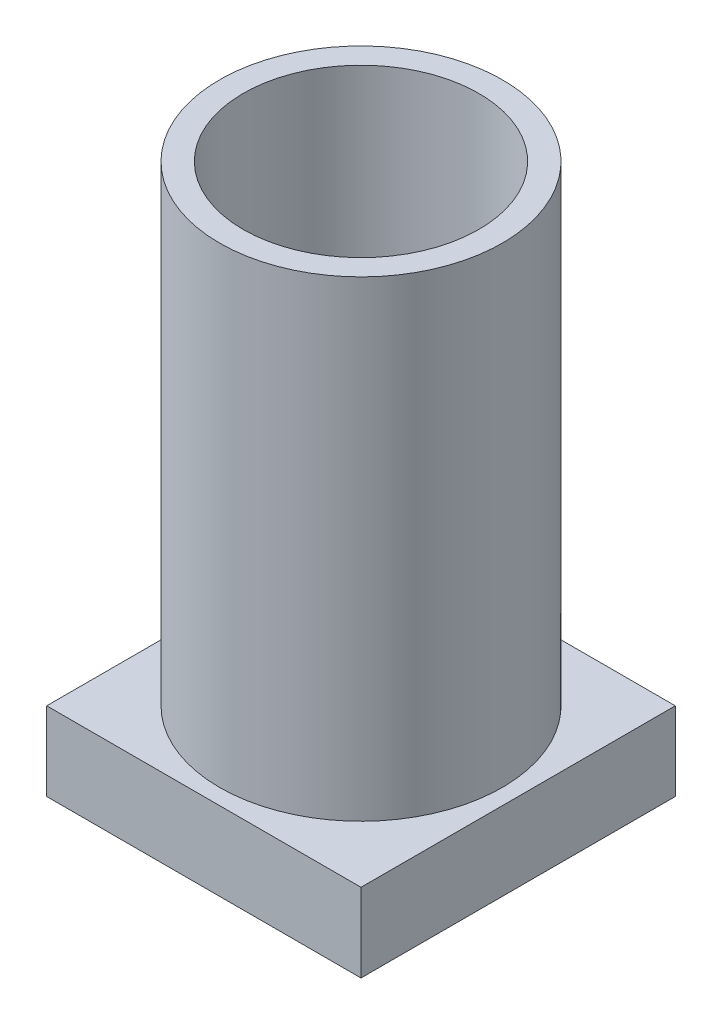
SolidWorks part; units mm, degrees
material "1023 Carbon Steel Sheet (SS)"
ref_plane "Front Plane" through (0, 0, 0) normal (0, 0, 1) x (1, 0, 0)
ref_plane "Top Plane" through (0, 0, 0) normal (0, 1, 0) x (1, 0, 0)
ref_plane "Right Plane" through (0, 0, 0) normal (1, 0, 0) x (0, 0, -1)
sketch "Sketch1" plane through (0, 0, 0) normal (0, 1, 0) x (1, 0, 0)
  line L1 (0, 0) -> (40, 0)
  line L2 (0, 0) -> (0, -40)
  line L3 (0, -40) -> (40, -40)
  line L4 (40, 0) -> (40, -40)
  dimension "D1" = 40
  dimension "D2" = 40
extrude "Boss-Extrude1" add sketch "Sketch1" along normal blind 10
sketch "Sketch2" plane through (0, 10, 0) normal (0, 1, 0) x (1, 0, 0)
  line L0 (40, -40) -> (40, 0) construction
  line L1 (40, 0) -> (0, 0) construction
  circle A0 centre (20, -20) radius 15
  circle A1 centre (20, -20) radius 18
  dimension "D1" = 30
  dimension "D2" = 20
  dimension "D4" = 36
  dimension "D3" = 20
extrude "Boss-Extrude2" add sketch "Sketch2" along normal blind 60
